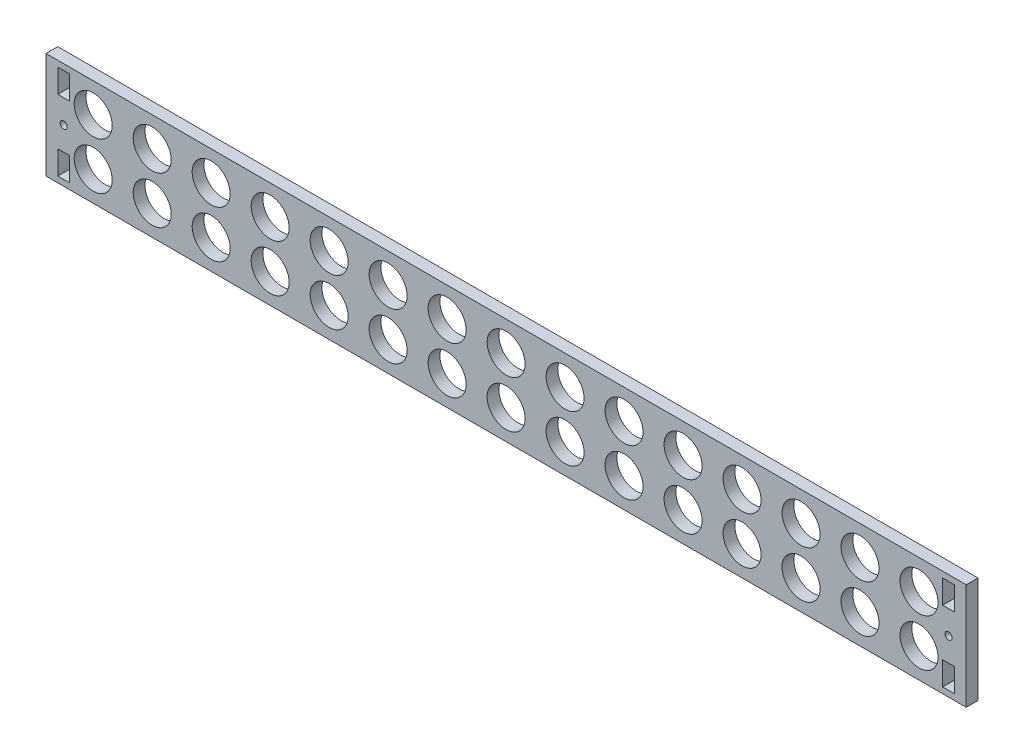
SolidWorks part; units mm, degrees
ref_plane "Front Plane" through (0, 0, 0) normal (0, 0, 1) x (1, 0, 0)
ref_plane "Top Plane" through (0, 0, 0) normal (0, 1, 0) x (1, 0, 0)
ref_plane "Right Plane" through (0, 0, 0) normal (1, 0, 0) x (0, 0, -1)
sketch "Sketch1" plane through (0, 0, 0) normal (0, 0, 1) x (1, 0, 0)
  line L0 (-90.218, 10) -> (299.3045, 10) construction
  line L1 (-85.8133, 22.5) -> (304.1867, 22.5)
  line L2 (-85.8133, 22.5) -> (-85.8133, -22.5)
  line L3 (-85.8133, -22.5) -> (304.1867, -22.5)
  line L4 (304.1867, 22.5) -> (304.1867, -22.5)
  line L5 (-80.8133, -10) -> (-75.8133, -10)
  line L6 (-91.3268, 0) -> (299.3045, 0) construction
  line L7 (-80.8133, 20) -> (-75.8133, 20)
  line L8 (-80.8133, 20) -> (-80.8133, 10)
  line L9 (-80.8133, 10) -> (-75.8133, 10)
  line L10 (-75.8133, 20) -> (-75.8133, 10)
  line L11 (-75.8133, -20) -> (-75.8133, -10)
  line L12 (-80.8133, -20) -> (-75.8133, -20)
  line L13 (-80.8133, -20) -> (-80.8133, -10)
  line L14 (109.1867, 30.0157) -> (109.1867, -45.8134) construction
  line L15 (-78.3133, 24.0051) -> (-78.3133, -32.23) construction
  line L16 (299.1867, -20) -> (299.1867, -10)
  line L17 (299.1867, -20) -> (294.1867, -20)
  line L18 (294.1867, -20) -> (294.1867, -10)
  line L19 (299.1867, -10) -> (294.1867, -10)
  line L20 (299.1867, 10) -> (294.1867, 10)
  line L21 (294.1867, 20) -> (294.1867, 10)
  line L22 (299.1867, 20) -> (294.1867, 20)
  line L23 (299.1867, 20) -> (299.1867, 10)
  circle A1 centre (-65.8133, 10) radius 8.05
  circle A2 centre (-40.8133, 10) radius 8.05
  circle A3 centre (-15.8133, 10) radius 8.05
  circle A4 centre (9.1867, 10) radius 8.05
  circle A5 centre (34.1867, 10) radius 8.05
  circle A6 centre (59.1867, 10) radius 8.05
  circle A7 centre (84.1867, 10) radius 8.05
  circle A8 centre (109.1867, 10) radius 8.05
  circle A9 centre (134.1867, 10) radius 8.05
  circle A10 centre (159.1867, 10) radius 8.05
  circle A11 centre (184.1867, 10) radius 8.05
  circle A12 centre (209.1867, 10) radius 8.05
  circle A13 centre (234.1867, 10) radius 8.05
  circle A14 centre (259.1867, 10) radius 8.05
  circle A15 centre (284.1867, 10) radius 8.05
  circle A16 centre (284.1867, -10) radius 8.05
  circle A17 centre (259.1867, -10) radius 8.05
  circle A18 centre (234.1867, -10) radius 8.05
  circle A19 centre (209.1867, -10) radius 8.05
  circle A20 centre (184.1867, -10) radius 8.05
  circle A21 centre (159.1867, -10) radius 8.05
  circle A22 centre (134.1867, -10) radius 8.05
  circle A23 centre (109.1867, -10) radius 8.05
  circle A24 centre (84.1867, -10) radius 8.05
  circle A25 centre (59.1867, -10) radius 8.05
  circle A26 centre (34.1867, -10) radius 8.05
  circle A27 centre (9.1867, -10) radius 8.05
  circle A28 centre (-15.8133, -10) radius 8.05
  circle A29 centre (-40.8133, -10) radius 8.05
  circle A30 centre (-65.8133, -10) radius 8.05
  circle A31 centre (-78.3133, 0) radius 1.5
  circle A32 centre (296.6867, 0) radius 1.5
  point P13 (-85.8133, 0)
  point P82 (-78.3133, 20)
  dimension "D5" = 20
  dimension "D1" = 45
  dimension "D2" = 390
  dimension "D3" = 12.5
  dimension "D4" = 10
  dimension "D7" = 5
  dimension "D8" = 5
  dimension "D6" = 15
extrude "Boss-Extrude1" add sketch "Sketch1" along normal blind 5
